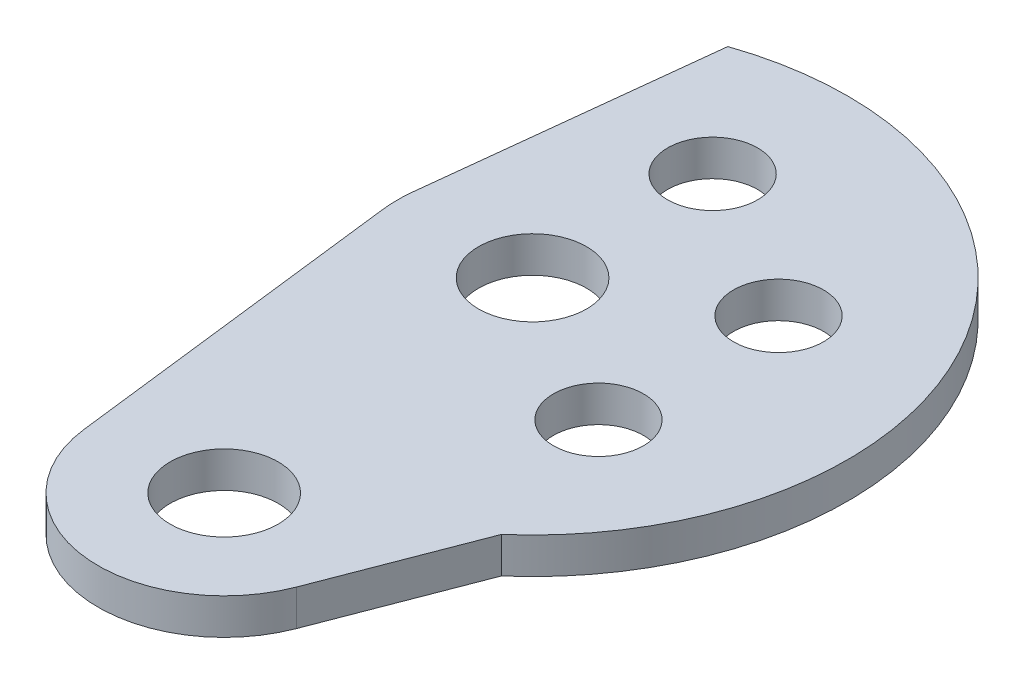
SolidWorks part; units mm, degrees
ref_plane "前视基准面" through (0, 0, 0) normal (0, 0, 1) x (1, 0, 0)
ref_plane "上视基准面" through (0, 0, 0) normal (0, 1, 0) x (1, 0, 0)
ref_plane "右视基准面" through (0, 0, 0) normal (1, 0, 0) x (0, 0, -1)
other "Configuration Table"
sketch "草图1" plane through (0, 0, 0) normal (0, 1, 0) x (1, 0, 0)
  line L0 (8.6603, 5) -> (0, 0) construction
  line L1 (8.6603, -5) -> (0, 0) construction
  line L2 (0, 0) -> (0, 9.8456) construction
  line L3 (-5.7023, 16.5449) -> (-7.4538, 0.8308)
  line L4 (-3.0074, -6.8706) -> (11.4771, -13.2108)
  circle A0 centre (0, 0) radius 10 construction
  circle A1 centre (0, 10) radius 2.5
  circle A2 centre (8.6603, -5) radius 2.5
  circle A3 centre (8.6603, 5) radius 2.5
  circle A4 centre (0, 0) radius 17.5
  circle A5 centre (0, 0) radius 7.5
  dimension "D1" = 20
  dimension "D2" = 5
  dimension "D3" = 5
  dimension "D5" = 5
  dimension "D6" = 35
  dimension "D8" = 15
  dimension "D4" = 60
  dimension "D7" = 60
  dimension "D9" = 53.64
  dimension "D10" = 53.64
extrude "凸台-拉伸1" add sketch "草图1" along normal blind 2 contours A5 | A5 A2 L4 A4 L3 A1 A3
sketch "草图2" plane through (0, 2, 0) normal (0, 1, 0) x (1, 0, 0)
  line L0 (-6.5824, -3.5948) -> (1.7849, -18.916) construction
  line L1 (-5.7023, 16.5449) -> (-7.4538, 0.8308) construction
  line L2 (-7.4457, -0.9008) -> (-5.1644, -19.7567)
  line L3 (11.4771, -13.2108) -> (8.3188, -21.4275)
  line L4 (-3.0074, -6.8706) -> (11.4771, -13.2108)
  line L5 (-5.7023, 16.5449) -> (-7.4538, 0.8308)
  line L6 (-3.0074, -6.8706) -> (11.4771, -13.2108)
  line L7 (-5.7023, 16.5449) -> (-7.4538, 0.8308)
  arc A1 (-7.4538, 0.8308) -> (-3.0074, -6.8706) centre (0, 0) ccw construction
  circle A2 centre (1.7849, -18.916) radius 7
  circle A3 centre (1.7849, -18.916) radius 3
  arc A4 (-7.4538, 0.8308) -> (-3.0074, -6.8706) centre (0, 0) ccw
  arc A5 (11.4771, -13.2108) -> (-5.7023, 16.5449) centre (0, 0) ccw
  arc A6 (-7.4538, 0.8308) -> (-3.0074, -6.8706) centre (0, 0) ccw
  arc A7 (11.4771, -13.2108) -> (-5.7023, 16.5449) centre (0, 0) ccw
  dimension "D4" = 14
  dimension "D5" = 6
  dimension "D1" = 145
  dimension "D3" = 19
  dimension "D2" = 0
extrude "凸台-拉伸2" add sketch "草图2" against normal blind 2
sketch "草图3" plane through (0, 2, 0) normal (0, 1, 0) x (1, 0, 0)
  circle A0 centre (0, 0) radius 3
  dimension "D1" = 6
extrude "切除-拉伸1" cut sketch "草图3" against normal blind 2
